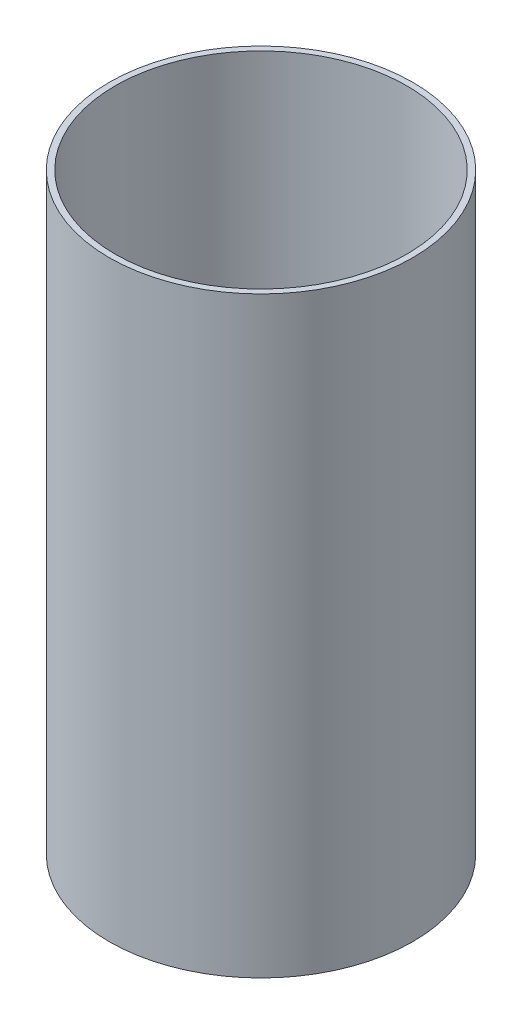
SolidWorks part; units mm, degrees
material "A-Glass Fiber"
ref_plane "Front Plane" through (0, 0, 0) normal (0, 0, 1) x (1, 0, 0)
ref_plane "Top Plane" through (0, 0, 0) normal (0, 1, 0) x (1, 0, 0)
ref_plane "Right Plane" through (0, 0, 0) normal (1, 0, 0) x (0, 0, -1)
sketch "Sketch1" plane through (0, 0, 0) normal (0, 1, 0) x (1, 0, 0)
  circle A0 centre (0, 0) radius 76
  circle A1 centre (0, 0) radius 73
  dimension "D1" = 152
  dimension "D2" = 3
extrude "Boss-Extrude1" add sketch "Sketch1" along normal blind 296.5
